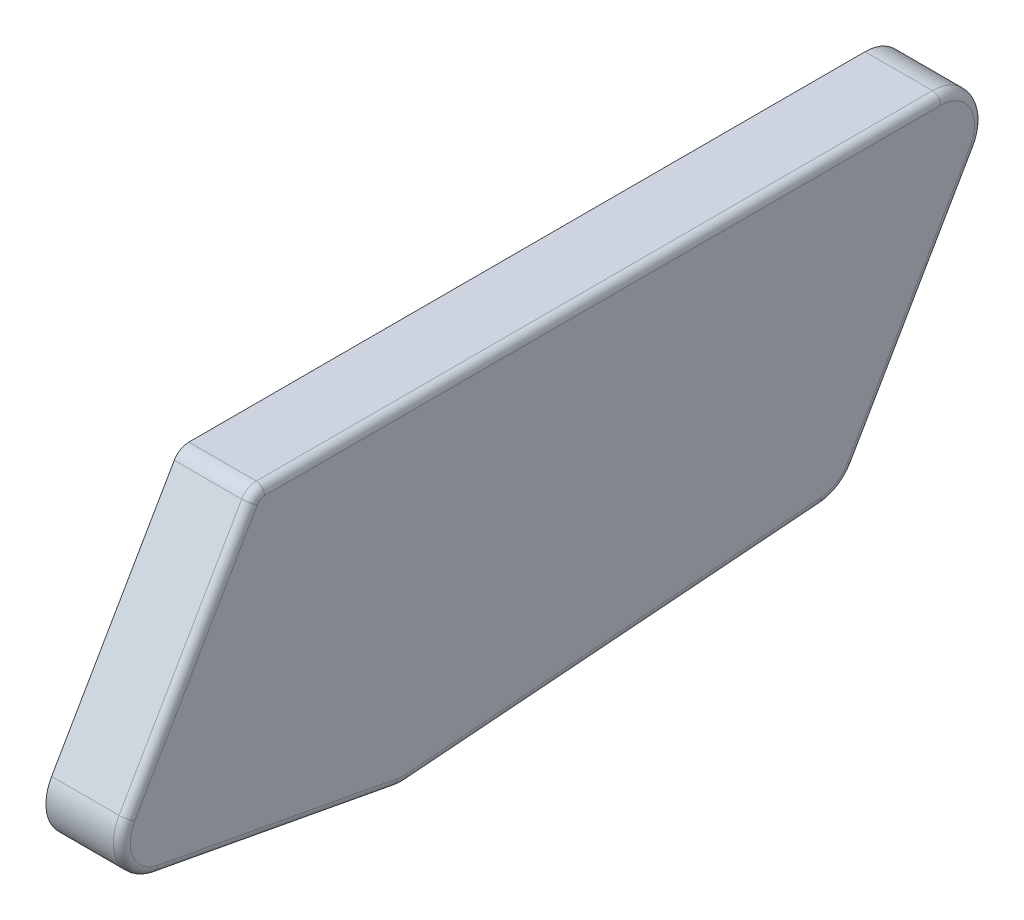
SolidWorks part; units mm, degrees
ref_plane "Front Plane" through (0, 0, 0) normal (0, 0, 1) x (1, 0, 0)
ref_plane "Top Plane" through (0, 0, 0) normal (0, 1, 0) x (1, 0, 0)
ref_plane "Right Plane" through (0, 0, 0) normal (1, 0, 0) x (0, 0, -1)
sketch "Sketch1" plane through (0, 0, 0) normal (1, 0, 0) x (0, 0, -1)
  line L0 (-40.1258, 0) -> (40.1258, 0)
  line L1 (44.456, -7.5) -> (29.8964, -32.7179)
  line L2 (25.9516, -35.2031) -> (-23.2933, -39.0094)
  line L3 (-24.5967, -38.9393) -> (-53.0054, -33.6329)
  line L4 (-56.4175, -26.2179) -> (-41.8579, -1)
  arc A0 (-24.5967, -38.9393) -> (-23.2933, -39.0094) centre (-23.6787, -34.0243) ccw
  arc A1 (25.9516, -35.2031) -> (29.8964, -32.7179) centre (25.5663, -30.2179) ccw
  arc A2 (44.456, -7.5) -> (40.1258, 0) centre (40.1258, -5) ccw
  arc A3 (-41.8579, -1) -> (-40.1258, 0) centre (-40.1258, -2) cw
  arc A4 (-56.4175, -26.2179) -> (-53.0054, -33.6329) centre (-52.0874, -28.7179) ccw
  point P11 (-23.9497, -39.0602)
  point P14 (28.5788, -35)
  point P17 (48.7861, 0)
  point P23 (-59.9497, -32.3358)
  dimension "D6" = 5
  dimension "D7" = 5
  dimension "D8" = 78
  dimension "D1" = 2
  dimension "D2" = 120
  dimension "D3" = 36
  dimension "D4" = 35
  dimension "D5" = 165
extrude "Boss-Extrude1" add sketch "Sketch1" along normal mid plane 9
fillet "Fillet2" radius 1 10 edges at (4.5, -30.8081, 56.6295) (4.5, -36.2861, 38.8011) (4.5, -39.0171, 23.9473) (4.5, -37.1062, -1.3291) (4.5, -34.4484, -28.2314) (4.5, -20.109, -37.1762) (4.5, -2.5, -44.456) (4.5, 0, 0) (4.5, -0.2679, 41.1258) (4.5, -13.609, 49.1377)
shell "Shell1" thickness 0.5
